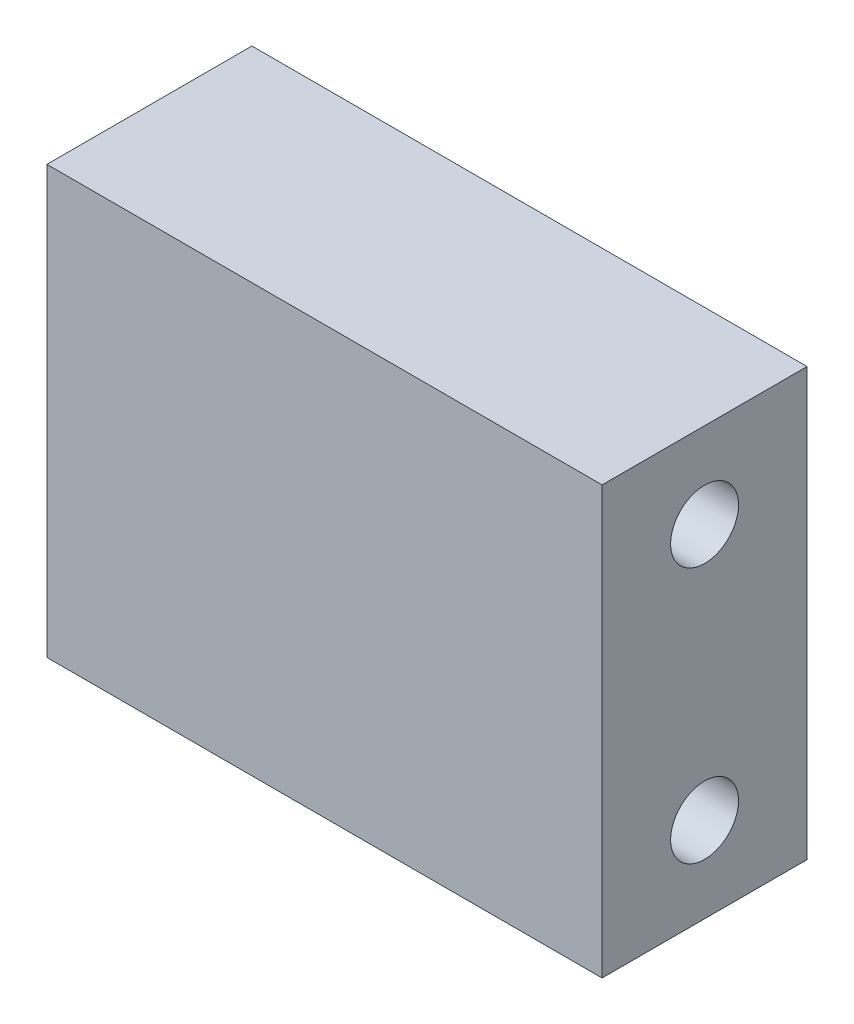
SolidWorks part; units mm, degrees
material "6061-T6 (SS)"
ref_plane "Front Plane" through (0, 0, 0) normal (0, 0, 1) x (1, 0, 0)
ref_plane "Top Plane" through (0, 0, 0) normal (0, 1, 0) x (1, 0, 0)
ref_plane "Right Plane" through (0, 0, 0) normal (1, 0, 0) x (0, 0, -1)
sketch "Sketch1" plane through (0, 0, 0) normal (1, 0, 0) x (0, 0, -1)
  line L1 (-6.096, 12.7) -> (6.096, 12.7)
  line L2 (-6.096, 12.7) -> (-6.096, -12.7)
  line L3 (-6.096, -12.7) -> (6.096, -12.7)
  line L4 (6.096, 12.7) -> (6.096, -12.7)
  line L5 (-6.096, 12.7) -> (6.096, -12.7) construction
  line L6 (-6.096, -12.7) -> (6.096, 12.7) construction
  point P0 (0, 0)
  dimension "D1" = 12.192
  dimension "D2" = 25.4
extrude "Boss-Extrude1" add sketch "Sketch1" along normal mid plane 33.02
sketch "Sketch2" plane through (16.51, 0, 0) normal (1, 0, 0) x (0, 0, -1)
  line L0 (0, 7.62) -> (0, -7.62) construction
  point P3 (0, 0)
  dimension "D1" = 15.24
hole_wizard "Tap Drill for #10-32 Tap1" positions "Sketch3" profile "Sketch4" hole size "#10-32" standard "ANSI Inch"
sketch "Sketch3" plane through (16.51, 0, 0) normal (1, 0, 0) x (0, 0, -1)
  point P0 (0, 7.62)
  point P3 (0, -7.62)
sketch "Sketch4" plane through (16.51, 7.62, 0) normal (0, 1, 0) x (0, 0, -1)
  line L0 (0, 0) -> (0, 11.3733)
  line L1 (0, 11.3733) -> (2.0193, 10.16)
  line L2 (2.0193, 10.16) -> (2.0193, 0)
  line L5 (2.0193, 0) -> (0, 0)
  line L10 (0, 11.3733) -> (-2.0193, 10.16) construction
  line L11 (0, -6.35) -> (0, 107.95) construction
  dimension "Hole Dia." = 4.0386
  dimension "Hole Depth" = 10.16
  dimension "Drill Angle" = 118
mirror "Mirror1" about plane through (0, 0, 0) normal (1, 0, 0) of "Tap Drill for #10-32 Tap1"
